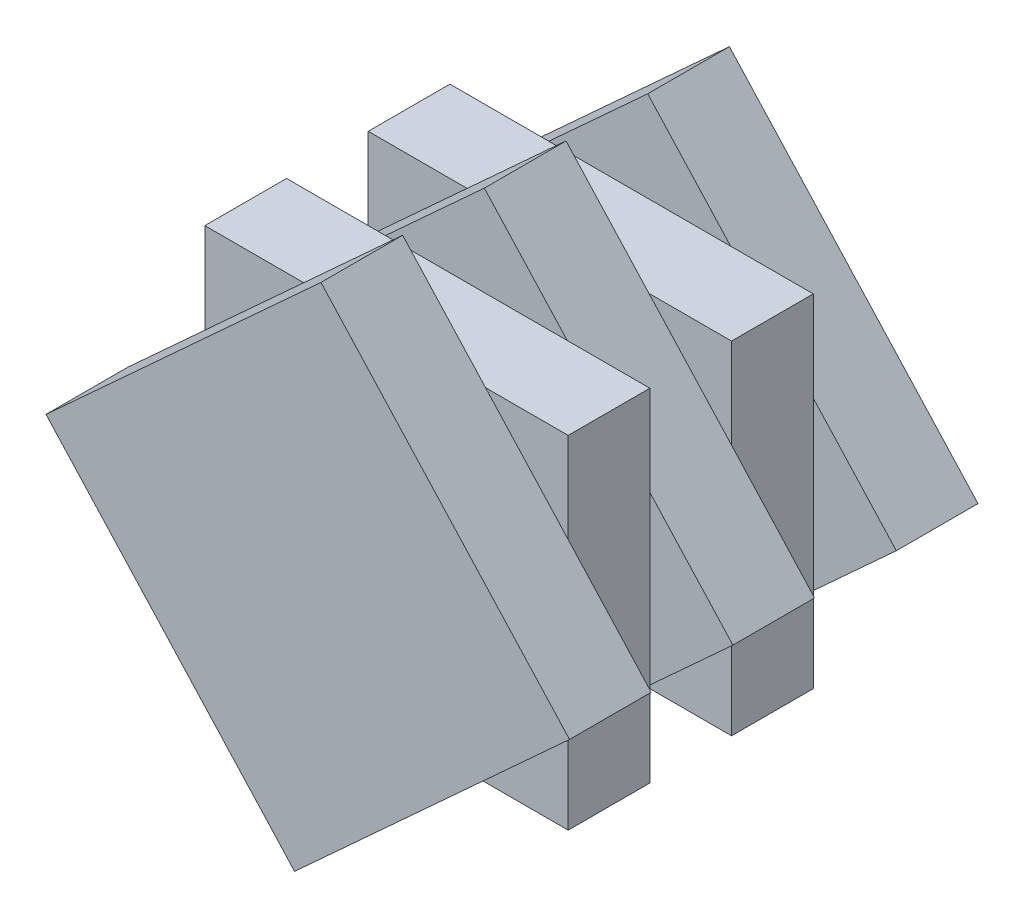
SolidWorks part; units mm, degrees
ref_plane "Alzado" through (0, 0, 0) normal (0, 0, 1) x (1, 0, 0)
ref_plane "Planta" through (0, 0, 0) normal (0, 1, 0) x (1, 0, 0)
ref_plane "Vista lateral" through (0, 0, 0) normal (1, 0, 0) x (0, 0, -1)
sketch "Croquis1" plane through (0, 0, 0) normal (0, 0, 1) x (1, 0, 0)
  line L1 (-55.5984, 52.3151) -> (55.5984, 52.3151)
  line L2 (-55.5984, 52.3151) -> (-55.5984, -52.3151)
  line L3 (-55.5984, -52.3151) -> (55.5984, -52.3151)
  line L4 (55.5984, 52.3151) -> (55.5984, -52.3151)
  line L5 (-55.5984, 52.3151) -> (55.5984, -52.3151) construction
  line L6 (-55.5984, -52.3151) -> (55.5984, 52.3151) construction
  point P0 (0, 0)
extrude "Saliente-Extruir1" add sketch "Croquis1" along normal blind 25
sketch "Croquis2" plane through (0, 0, 25) normal (0, 0, 1) x (1, 0, 0)
  line L0 (-3.1328, -80.1038) -> (81.0116, -3.0591)
  line L1 (-3.1328, -80.1038) -> (-79.2066, 2.9802)
  line L2 (81.0116, -3.0591) -> (4.9378, 80.0249)
  line L3 (-79.2066, 2.9802) -> (4.9378, 80.0249)
  point P0 (-3.1328, -80.1038)
extrude "Saliente-Extruir2" add sketch "Croquis2" along normal blind 25
pattern_linear "MatrizL4" count 2 spacing 50 along (0, 0, 1) of "Saliente-Extruir1", "Saliente-Extruir2"
pattern_linear "MatrizL5" count 2 spacing 50 along (0, 0, -1) of "Saliente-Extruir1", "Saliente-Extruir2"
sketch "Croquis3" plane through (0, 0, -25) normal (0, 0, -1) x (-1, 0, 0)
  circle A1 centre (0, 0) radius 50.7931
extrude "Cortar-Extruir4" cut sketch "Croquis3" against normal blind 120
